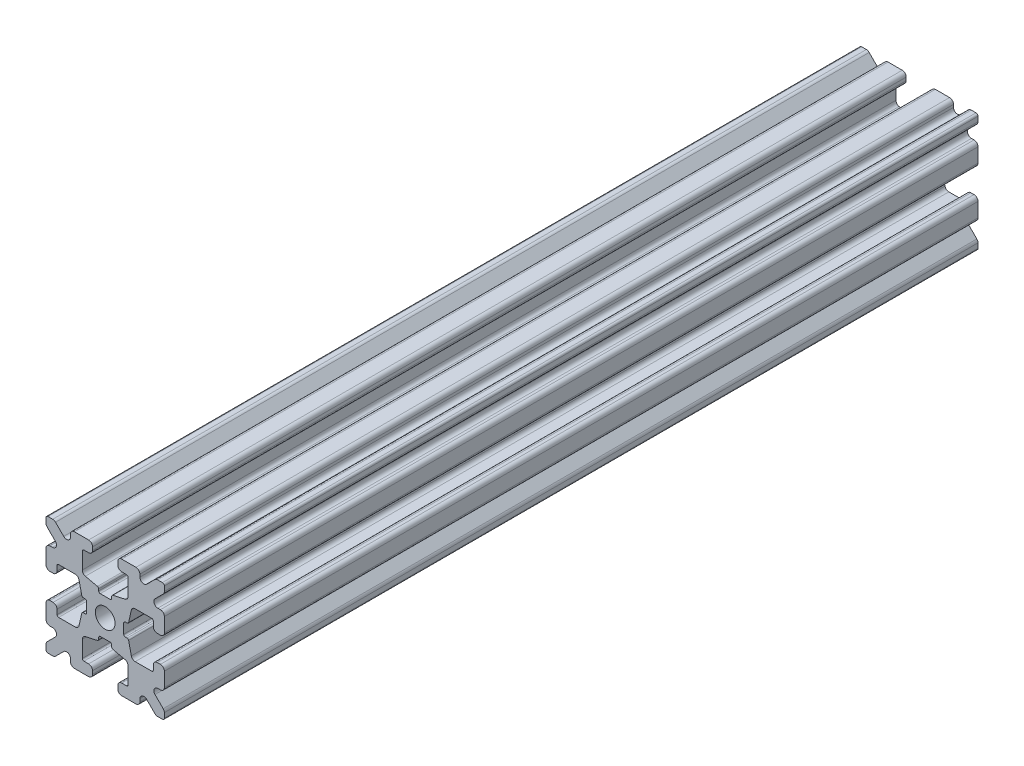
SolidWorks part; units mm, degrees
material "6061-T6 (SS)"
ref_plane "Front Plane" through (0, 0, 0) normal (0, 0, 1) x (1, 0, 0)
ref_plane "Top Plane" through (0, 0, 0) normal (0, 1, 0) x (1, 0, 0)
ref_plane "Right Plane" through (0, 0, 0) normal (1, 0, 0) x (0, 0, -1)
ref_plane "Plane1" through (0, 0, 150) normal (0, 0, 1) x (1, 0, 0)
sketch "Sketch1" plane through (0, 0, 150) normal (0, 0, 1) x (1, 0, 0)
  line L0 (0.9818, -2.97) -> (2.5094, -3.3124)
  line L1 (2.9, -3.8003) -> (2.9, -5.9)
  line L2 (2.7, -6.1) -> (2.1, -6.1)
  line L3 (1.6, -6.6) -> (1.6, -7)
  line L4 (2.1, -7.5) -> (3.9, -7.5)
  line L5 (4.4, -7) -> (4.4, -6.6678)
  line L6 (5.2536, -6.3142) -> (6.2929, -7.3536)
  line L7 (6.6464, -7.5) -> (7.25, -7.5)
  line L8 (7.5, -7.25) -> (7.5, -6.6464)
  line L9 (7.3536, -6.2929) -> (6.3142, -5.2536)
  line L10 (6.6678, -4.4) -> (7, -4.4)
  line L11 (7.5, -3.9) -> (7.5, -2.1)
  line L12 (7, -1.6) -> (6.6, -1.6)
  line L13 (6.1, -2.1) -> (6.1, -2.7)
  line L14 (5.9, -2.9) -> (3.8003, -2.9)
  line L15 (3.3124, -2.5094) -> (2.97, -0.9818)
  line L16 (2.7749, -0.8255) -> (2.5471, -0.8255)
  line L17 (2.3471, -0.6255) -> (2.3471, 0.6255)
  line L18 (2.5471, 0.8255) -> (2.7749, 0.8255)
  line L19 (2.97, 0.9818) -> (3.3124, 2.5094)
  line L20 (3.8003, 2.9) -> (5.9, 2.9)
  line L21 (6.1, 2.7) -> (6.1, 2.1)
  line L22 (6.6, 1.6) -> (7, 1.6)
  line L23 (7.5, 2.1) -> (7.5, 3.9)
  line L24 (7, 4.4) -> (6.6678, 4.4)
  line L25 (6.3142, 5.2536) -> (7.3536, 6.2929)
  line L26 (7.5, 6.6464) -> (7.5, 7.25)
  line L27 (7.25, 7.5) -> (6.6464, 7.5)
  line L28 (6.2929, 7.3536) -> (5.2536, 6.3142)
  line L29 (4.4, 6.6678) -> (4.4, 7)
  line L30 (3.9, 7.5) -> (2.1, 7.5)
  line L31 (1.6, 7) -> (1.6, 6.6)
  line L32 (2.1, 6.1) -> (2.7, 6.1)
  line L33 (2.9, 5.9) -> (2.9, 3.8003)
  line L34 (2.5094, 3.3124) -> (0.9818, 2.97)
  line L35 (0.8255, 2.7749) -> (0.8255, 2.5471)
  line L36 (0.6255, 2.3471) -> (-0.6255, 2.3471)
  line L37 (-0.8255, 2.5471) -> (-0.8255, 2.7749)
  line L38 (-0.9818, 2.97) -> (-2.5094, 3.3124)
  line L39 (-2.9, 3.8003) -> (-2.9, 5.9)
  line L40 (-2.7, 6.1) -> (-2.1, 6.1)
  line L41 (-1.6, 6.6) -> (-1.6, 7)
  line L42 (-2.1, 7.5) -> (-3.9, 7.5)
  line L43 (-4.4, 7) -> (-4.4, 6.6678)
  line L44 (-5.2536, 6.3142) -> (-6.2929, 7.3536)
  line L45 (-6.6464, 7.5) -> (-7.25, 7.5)
  line L46 (-7.5, 7.25) -> (-7.5, 6.6464)
  line L47 (-7.3536, 6.2929) -> (-6.3142, 5.2536)
  line L48 (-6.6678, 4.4) -> (-7, 4.4)
  line L49 (-7.5, 3.9) -> (-7.5, 2.1)
  line L50 (-7, 1.6) -> (-6.6, 1.6)
  line L51 (-6.1, 2.1) -> (-6.1, 2.7)
  line L52 (-5.9, 2.9) -> (-3.8003, 2.9)
  line L53 (-3.3124, 2.5094) -> (-2.97, 0.9818)
  line L54 (-2.7749, 0.8255) -> (-2.5471, 0.8255)
  line L55 (-2.3471, 0.6255) -> (-2.3471, -0.6255)
  line L56 (-2.5471, -0.8255) -> (-2.7749, -0.8255)
  line L57 (-2.97, -0.9818) -> (-3.3124, -2.5094)
  line L58 (-3.8003, -2.9) -> (-5.9, -2.9)
  line L59 (-6.1, -2.7) -> (-6.1, -2.1)
  line L60 (-6.6, -1.6) -> (-7, -1.6)
  line L61 (-7.5, -2.1) -> (-7.5, -3.9)
  line L62 (-7, -4.4) -> (-6.6678, -4.4)
  line L63 (-6.3142, -5.2536) -> (-7.3536, -6.2929)
  line L64 (-7.5, -6.6464) -> (-7.5, -7.25)
  line L65 (-7.25, -7.5) -> (-6.6464, -7.5)
  line L66 (-6.2929, -7.3536) -> (-5.2536, -6.3142)
  line L67 (-4.4, -6.6678) -> (-4.4, -7)
  line L68 (-3.9, -7.5) -> (-2.1, -7.5)
  line L69 (-1.6, -7) -> (-1.6, -6.6)
  line L70 (-2.1, -6.1) -> (-2.7, -6.1)
  line L71 (-2.9, -5.9) -> (-2.9, -3.8003)
  line L72 (-2.5094, -3.3124) -> (-0.9818, -2.97)
  line L73 (-0.8255, -2.7749) -> (-0.8255, -2.5471)
  line L74 (-0.6255, -2.3471) -> (0.6255, -2.3471)
  line L75 (0.8255, -2.5471) -> (0.8255, -2.7749)
  circle A0 centre (0, 0) radius 1.25
  arc A1 (0.8255, -2.7749) -> (0.9818, -2.97) centre (1.0255, -2.7749) ccw
  arc A2 (2.5094, -3.3124) -> (2.9, -3.8003) centre (2.4, -3.8003) cw
  arc A3 (2.9, -5.9) -> (2.7, -6.1) centre (2.7, -5.9) cw
  arc A4 (2.1, -6.1) -> (1.6, -6.6) centre (2.1, -6.6) ccw
  arc A5 (1.6, -7) -> (2.1, -7.5) centre (2.1, -7) ccw
  arc A6 (3.9, -7.5) -> (4.4, -7) centre (3.9, -7) ccw
  arc A7 (4.4, -6.6678) -> (5.2536, -6.3142) centre (4.9, -6.6678) cw
  arc A8 (6.2929, -7.3536) -> (6.6464, -7.5) centre (6.6464, -7) ccw
  arc A9 (7.25, -7.5) -> (7.5, -7.25) centre (7.25, -7.25) ccw
  arc A10 (7.5, -6.6464) -> (7.3536, -6.2929) centre (7, -6.6464) ccw
  arc A11 (6.3142, -5.2536) -> (6.6678, -4.4) centre (6.6678, -4.9) cw
  arc A12 (7, -4.4) -> (7.5, -3.9) centre (7, -3.9) ccw
  arc A13 (7.5, -2.1) -> (7, -1.6) centre (7, -2.1) ccw
  arc A14 (6.6, -1.6) -> (6.1, -2.1) centre (6.6, -2.1) ccw
  arc A15 (6.1, -2.7) -> (5.9, -2.9) centre (5.9, -2.7) cw
  arc A16 (3.8003, -2.9) -> (3.3124, -2.5094) centre (3.8003, -2.4) cw
  arc A17 (2.97, -0.9818) -> (2.7749, -0.8255) centre (2.7749, -1.0255) ccw
  arc A18 (2.5471, -0.8255) -> (2.3471, -0.6255) centre (2.5471, -0.6255) cw
  arc A19 (2.3471, 0.6255) -> (2.5471, 0.8255) centre (2.5471, 0.6255) cw
  arc A20 (2.7749, 0.8255) -> (2.97, 0.9818) centre (2.7749, 1.0255) ccw
  arc A21 (3.3124, 2.5094) -> (3.8003, 2.9) centre (3.8003, 2.4) cw
  arc A22 (5.9, 2.9) -> (6.1, 2.7) centre (5.9, 2.7) cw
  arc A23 (6.1, 2.1) -> (6.6, 1.6) centre (6.6, 2.1) ccw
  arc A24 (7, 1.6) -> (7.5, 2.1) centre (7, 2.1) ccw
  arc A25 (7.5, 3.9) -> (7, 4.4) centre (7, 3.9) ccw
  arc A26 (6.6678, 4.4) -> (6.3142, 5.2536) centre (6.6678, 4.9) cw
  arc A27 (7.3536, 6.2929) -> (7.5, 6.6464) centre (7, 6.6464) ccw
  arc A28 (7.5, 7.25) -> (7.25, 7.5) centre (7.25, 7.25) ccw
  arc A29 (6.6464, 7.5) -> (6.2929, 7.3536) centre (6.6464, 7) ccw
  arc A30 (5.2536, 6.3142) -> (4.4, 6.6678) centre (4.9, 6.6678) cw
  arc A31 (4.4, 7) -> (3.9, 7.5) centre (3.9, 7) ccw
  arc A32 (2.1, 7.5) -> (1.6, 7) centre (2.1, 7) ccw
  arc A33 (1.6, 6.6) -> (2.1, 6.1) centre (2.1, 6.6) ccw
  arc A34 (2.7, 6.1) -> (2.9, 5.9) centre (2.7, 5.9) cw
  arc A35 (2.9, 3.8003) -> (2.5094, 3.3124) centre (2.4, 3.8003) cw
  arc A36 (0.9818, 2.97) -> (0.8255, 2.7749) centre (1.0255, 2.7749) ccw
  arc A37 (0.8255, 2.5471) -> (0.6255, 2.3471) centre (0.6255, 2.5471) cw
  arc A38 (-0.6255, 2.3471) -> (-0.8255, 2.5471) centre (-0.6255, 2.5471) cw
  arc A39 (-0.8255, 2.7749) -> (-0.9818, 2.97) centre (-1.0255, 2.7749) ccw
  arc A40 (-2.5094, 3.3124) -> (-2.9, 3.8003) centre (-2.4, 3.8003) cw
  arc A41 (-2.9, 5.9) -> (-2.7, 6.1) centre (-2.7, 5.9) cw
  arc A42 (-2.1, 6.1) -> (-1.6, 6.6) centre (-2.1, 6.6) ccw
  arc A43 (-1.6, 7) -> (-2.1, 7.5) centre (-2.1, 7) ccw
  arc A44 (-3.9, 7.5) -> (-4.4, 7) centre (-3.9, 7) ccw
  arc A45 (-4.4, 6.6678) -> (-5.2536, 6.3142) centre (-4.9, 6.6678) cw
  arc A46 (-6.2929, 7.3536) -> (-6.6464, 7.5) centre (-6.6464, 7) ccw
  arc A47 (-7.25, 7.5) -> (-7.5, 7.25) centre (-7.25, 7.25) ccw
  arc A48 (-7.5, 6.6464) -> (-7.3536, 6.2929) centre (-7, 6.6464) ccw
  arc A49 (-6.3142, 5.2536) -> (-6.6678, 4.4) centre (-6.6678, 4.9) cw
  arc A50 (-7, 4.4) -> (-7.5, 3.9) centre (-7, 3.9) ccw
  arc A51 (-7.5, 2.1) -> (-7, 1.6) centre (-7, 2.1) ccw
  arc A52 (-6.6, 1.6) -> (-6.1, 2.1) centre (-6.6, 2.1) ccw
  arc A53 (-6.1, 2.7) -> (-5.9, 2.9) centre (-5.9, 2.7) cw
  arc A54 (-3.8003, 2.9) -> (-3.3124, 2.5094) centre (-3.8003, 2.4) cw
  arc A55 (-2.97, 0.9818) -> (-2.7749, 0.8255) centre (-2.7749, 1.0255) ccw
  arc A56 (-2.5471, 0.8255) -> (-2.3471, 0.6255) centre (-2.5471, 0.6255) cw
  arc A57 (-2.3471, -0.6255) -> (-2.5471, -0.8255) centre (-2.5471, -0.6255) cw
  arc A58 (-2.7749, -0.8255) -> (-2.97, -0.9818) centre (-2.7749, -1.0255) ccw
  arc A59 (-3.3124, -2.5094) -> (-3.8003, -2.9) centre (-3.8003, -2.4) cw
  arc A60 (-5.9, -2.9) -> (-6.1, -2.7) centre (-5.9, -2.7) cw
  arc A61 (-6.1, -2.1) -> (-6.6, -1.6) centre (-6.6, -2.1) ccw
  arc A62 (-7, -1.6) -> (-7.5, -2.1) centre (-7, -2.1) ccw
  arc A63 (-7.5, -3.9) -> (-7, -4.4) centre (-7, -3.9) ccw
  arc A64 (-6.6678, -4.4) -> (-6.3142, -5.2536) centre (-6.6678, -4.9) cw
  arc A65 (-7.3536, -6.2929) -> (-7.5, -6.6464) centre (-7, -6.6464) ccw
  arc A66 (-7.5, -7.25) -> (-7.25, -7.5) centre (-7.25, -7.25) ccw
  arc A67 (-6.6464, -7.5) -> (-6.2929, -7.3536) centre (-6.6464, -7) ccw
  arc A68 (-5.2536, -6.3142) -> (-4.4, -6.6678) centre (-4.9, -6.6678) cw
  arc A69 (-4.4, -7) -> (-3.9, -7.5) centre (-3.9, -7) ccw
  arc A70 (-2.1, -7.5) -> (-1.6, -7) centre (-2.1, -7) ccw
  arc A71 (-1.6, -6.6) -> (-2.1, -6.1) centre (-2.1, -6.6) ccw
  arc A72 (-2.7, -6.1) -> (-2.9, -5.9) centre (-2.7, -5.9) cw
  arc A73 (-2.9, -3.8003) -> (-2.5094, -3.3124) centre (-2.4, -3.8003) cw
  arc A74 (-0.9818, -2.97) -> (-0.8255, -2.7749) centre (-1.0255, -2.7749) ccw
  arc A75 (-0.8255, -2.5471) -> (-0.6255, -2.3471) centre (-0.6255, -2.5471) cw
  arc A76 (0.6255, -2.3471) -> (0.8255, -2.5471) centre (0.6255, -2.5471) cw
extrude "Boss-Extrude1" add sketch "Sketch1" against normal blind 103.1113
